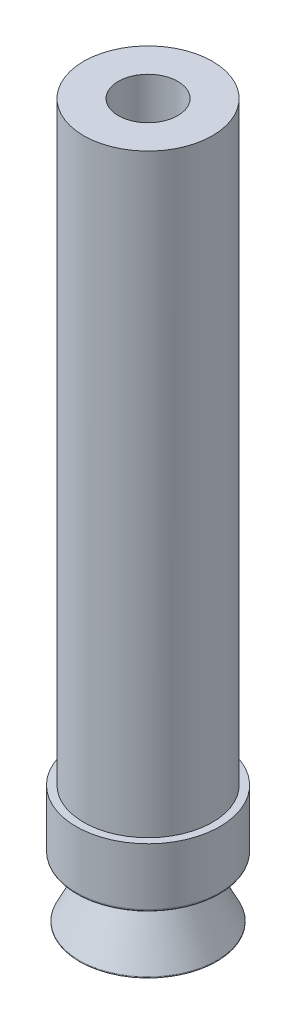
SolidWorks part; units mm, degrees
ref_plane "Front Plane" through (0, 0, 0) normal (0, 0, 1) x (1, 0, 0)
ref_plane "Top Plane" through (0, 0, 0) normal (0, 1, 0) x (1, 0, 0)
ref_plane "Right Plane" through (0, 0, 0) normal (1, 0, 0) x (0, 0, -1)
sketch "Sketch1" plane through (0, 0, 0) normal (0, 1, 0) x (1, 0, 0)
  circle A0 centre (0, 0) radius 6.5
  dimension "D1" = 13
extrude "Boss-Extrude1" add sketch "Sketch1" along normal blind 60
sketch "Sketch2" plane through (0, 60, 0) normal (0, 1, 0) x (1, 0, 0)
  circle A0 centre (0, 0) radius 3
  dimension "D1" = 6
extrude "Inner Chamber" cut sketch "Sketch2" against normal blind 52.5
sketch "Sketch4" plane through (0, 0, 0) normal (0, -1, 0) x (1, 0, 0)
  circle A0 centre (0, 0) radius 7.25
  dimension "D1" = 14.5
extrude "Boss-Extrude2" add sketch "Sketch4" along normal blind 6 contours A0
sketch "Sketch6" plane through (0, 0, 0) normal (1, 0, 0) x (0, 0, -1)
  line L0 (0, -6) -> (1, -6)
  line L1 (-7.25, -6) -> (7.25, -6) construction
  line L2 (1, -6) -> (6.75, -12)
  line L3 (6.75, -12) -> (7, -12)
  line L4 (7, -12) -> (4, -6)
  line L5 (4, -6) -> (1, -6)
  line L6 (0, -6) -> (0, -13.9544)
  dimension "D1" = 4
  dimension "D2" = 1
  dimension "D3" = 6
  dimension "D4" = 0.25
  dimension "D5" = 7
  dimension "D6" = 0
revolve "Revolve1" add sketch "Sketch6" angle 360 about L6
fillet "Fillet4" radius 0.1 2 edges at (0, -12, 6.75) (0, -12, 7)
fillet "Fillet5" radius 0.25 1 edges at (0, -6, -7.25)
fillet "Fillet6" radius 0.25 1 edges at (0, -6, 4)
